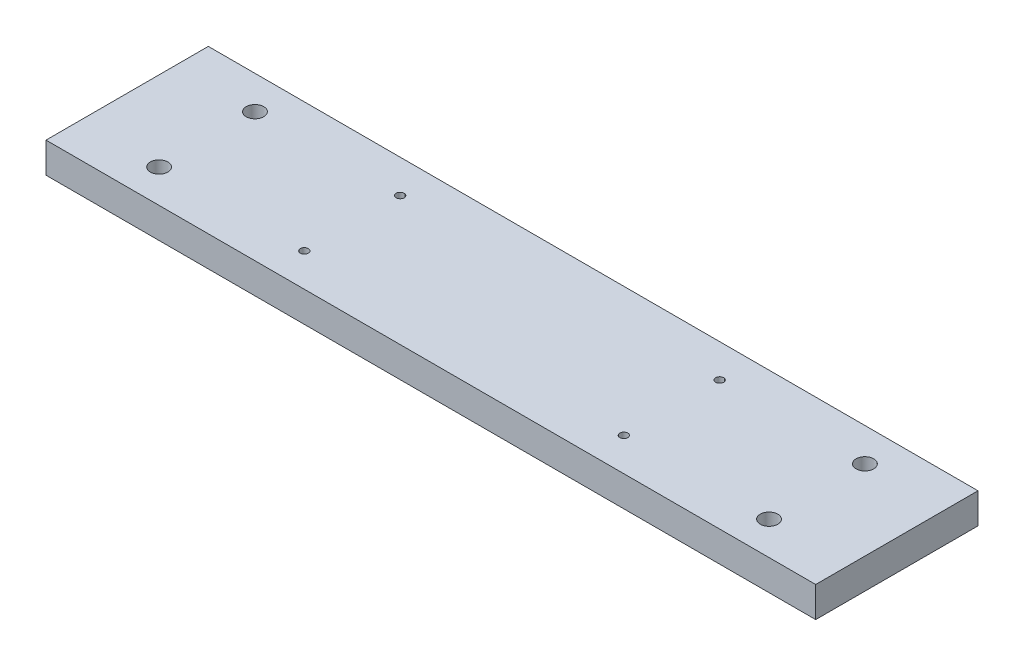
SolidWorks part; units mm, degrees
material "6061-T6 (SS)"
ref_plane "Front" through (0, 0, 0) normal (0, 0, 1) x (1, 0, 0)
ref_plane "Top" through (0, 0, 0) normal (0, 1, 0) x (1, 0, 0)
ref_plane "Right" through (0, 0, 0) normal (1, 0, 0) x (0, 0, -1)
sketch "Sketch1" plane through (0, 0, 0) normal (0, 1, 0) x (1, 0, 0)
  line L0 (0, -11.7989) -> (0, 14.9294) construction
  line L1 (-120.45, 25.4) -> (120.45, 25.4)
  line L2 (-120.45, 25.4) -> (-120.45, -25.4)
  line L3 (-120.45, -25.4) -> (120.45, -25.4)
  line L4 (120.45, 25.4) -> (120.45, -25.4)
  line L5 (-120.45, 25.4) -> (120.45, -25.4) construction
  line L6 (-120.45, -25.4) -> (120.45, 25.4) construction
  line L7 (-55, 20) -> (55, 20) construction
  line L8 (-55, 20) -> (-55, -20) construction
  line L9 (-55, -20) -> (55, -20) construction
  line L10 (55, 20) -> (55, -20) construction
  line L11 (-55, 20) -> (55, -20) construction
  line L12 (-55, -20) -> (55, 20) construction
  line L13 (-80, 25.4) -> (-60, 25.4) construction
  line L14 (-80, 25.4) -> (-80, -25.4) construction
  line L15 (-80, -25.4) -> (-60, -25.4) construction
  line L16 (-60, 25.4) -> (-60, -25.4) construction
  line L17 (60, 25.4) -> (80, 25.4) construction
  line L18 (60, 25.4) -> (60, -25.4) construction
  line L19 (60, -25.4) -> (80, -25.4) construction
  line L20 (80, 25.4) -> (80, -25.4) construction
  line L21 (-105.45, 25.4) -> (-85.45, 25.4) construction
  line L22 (-105.45, 25.4) -> (-105.45, -25.4) construction
  line L23 (-105.45, -25.4) -> (-85.45, -25.4) construction
  line L24 (-85.45, 25.4) -> (-85.45, -25.4) construction
  line L25 (85.45, 25.4) -> (105.45, 25.4) construction
  line L26 (85.45, 25.4) -> (85.45, -25.4) construction
  line L27 (85.45, -25.4) -> (105.45, -25.4) construction
  line L28 (105.45, 25.4) -> (105.45, -25.4) construction
  line L29 (-85.45, 9.85) -> (-80, 9.85) construction
  line L30 (-85.45, 9.85) -> (-85.45, -9.85) construction
  line L31 (-85.45, -9.85) -> (-80, -9.85) construction
  line L32 (-80, 9.85) -> (-80, -9.85) construction
  line L33 (80, 9.85) -> (80, -9.85) construction
  line L34 (85.45, -9.85) -> (80, -9.85) construction
  line L35 (85.45, 9.85) -> (85.45, -9.85) construction
  line L36 (85.45, 9.85) -> (80, 9.85) construction
  point P0 (0, 0)
  point P6 (0, 0)
  point P33 (-80, 0)
  point P34 (-80, 0)
  dimension "D1" = 40
  dimension "D2" = 50.8
  dimension "D3" = 110
  dimension "D4" = 20
  dimension "D5" = 20
  dimension "D6" = 5
  dimension "D7" = 5
  dimension "D8" = 20
  dimension "D9" = 20
  dimension "D10" = 5.45
  dimension "D11" = 19.7
  dimension "D12" = 15
extrude "Boss-Extrude1" add sketch "Sketch1" against normal blind 9.525
hole_wizard "M3x0.5 Tapped Hole1" positions "Sketch2" profile "Sketch4" tap size "M3x0.5" standard "ANSI Metric" end condition through all
sketch "Sketch2" plane through (0, 0, 0) normal (0, 1, 0) x (1, 0, 0)
  line L0 (-55, 20) -> (55, 20) construction
  line L1 (-55, 20) -> (-55, -20) construction
  line L2 (-55, -20) -> (55, -20) construction
  line L3 (55, 20) -> (55, -20) construction
  point P0 (-50, 15)
  point P2 (-50, -15)
  point P4 (50, -15)
  point P6 (50, 15)
  dimension "D1" = 5
  dimension "D2" = 5
  dimension "D3" = 5
  dimension "D4" = 5
sketch "Sketch4" plane through (-50, 0, -15) normal (1, 0, 0) x (0, 0, 1)
  line L0 (0, 0) -> (0, 9.525)
  line L1 (0, 9.525) -> (1.25, 9.525)
  line L2 (1.25, 9.525) -> (1.25, 0)
  line L5 (1.25, 0) -> (0, 0)
  line L11 (0, -6.35) -> (0, 107.95) construction
  dimension "Thru Tap Drill Dia." = 2.5
  dimension "Thru Tap Drill Depth" = 9.525
cosmetic thread "Hole Thread1" parameters "D2"=3
cosmetic thread "Hole Thread2" parameters "D2"=3
cosmetic thread "Hole Thread3" parameters "D2"=3
cosmetic thread "Hole Thread4" parameters "D2"=3
hole_wizard "M5 Clearance Hole1" positions "Sketch5" profile "Sketch7" hole size "M5" standard "ANSI Metric" end condition through all
sketch "Sketch5" plane through (0, 0, 0) normal (0, 1, 0) x (1, 0, 0)
  line L2 (-105.45, 0) -> (-85.45, 0)
  line L3 (-105.45, 25.4) -> (-105.45, -25.4) construction
  line L4 (-85.45, 25.4) -> (-85.45, -25.4) construction
  line L11 (-95.45, 15) -> (-95.45, -15)
  line L12 (0, -11.7989) -> (0, 14.9294) construction
  line L13 (0, -11.7989) -> (0, 14.9294)
  point P24 (-95.45, 15)
  point P25 (-95.45, -15)
  point P30 (-95.45, 0)
  point P46 (95.45, -15)
  point P49 (95.45, 15)
  dimension "D1" = 30
sketch "Sketch7" plane through (95.45, 0, -15) normal (1, 0, 0) x (0, 0, 1)
  line L0 (0, 0) -> (0, 9.525)
  line L1 (0, 9.525) -> (2.75, 9.525)
  line L2 (2.75, 9.525) -> (2.75, 0)
  line L5 (2.75, 0) -> (0, 0)
  line L11 (0, -6.35) -> (0, 107.95) construction
  dimension "Thru Hole Dia." = 5.5
  dimension "Thru Hole Depth" = 9.525
